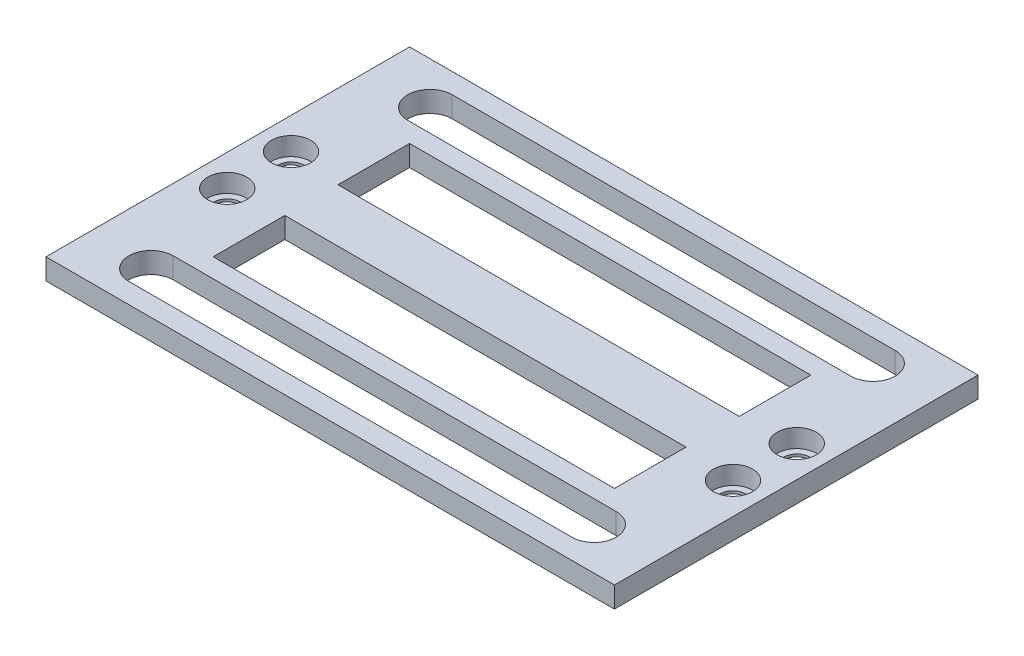
SolidWorks part; units mm, degrees
material "PLA"
ref_plane "Front Plane" through (0, 0, 0) normal (0, 0, 1) x (1, 0, 0)
ref_plane "Top Plane" through (0, 0, 0) normal (0, 1, 0) x (1, 0, 0)
ref_plane "Right Plane" through (0, 0, 0) normal (1, 0, 0) x (0, 0, -1)
sketch "Sketch1" plane through (0, 0, 0) normal (0, 1, 0) x (1, 0, 0)
  line L0 (-27.2, -17.399) -> (-21.2, -17.399) construction
  line L1 (-27.2, -17.399) -> (27.2, -17.399)
  line L2 (-27.2, -17.399) -> (-27.2, 17.399)
  line L3 (-27.2, 17.399) -> (27.2, 17.399)
  line L4 (27.2, -17.399) -> (27.2, 17.399)
  line L5 (-27.2, -17.399) -> (-21.2, -13.561) construction
  line L6 (-27.2, 17.399) -> (17.5466, -11.224) construction
  line L7 (-21.2, -17.399) -> (-21.2, -15.474) construction
  line L8 (-21.2, -15.474) -> (-21.2, -11.224) construction
  line L9 (0, -55) -> (0, 55) construction
  line L10 (-21.2, -11.224) -> (21.2, -11.224)
  line L11 (21.2, -15.474) -> (-21.2, -15.474)
  line L12 (-17.5466, -11.224) -> (27.2, 17.399) construction
  line L13 (22.8875, -14.6405) -> (27.2, -17.399) construction
  line L14 (-55, 0) -> (55, 0) construction
  line L15 (-21.2, 11.224) -> (21.2, 11.224)
  line L16 (21.2, 15.474) -> (-21.2, 15.474)
  line L17 (-21.2, -11.224) -> (-21.2, -9.3952) construction
  line L18 (-21.2, -9.3952) -> (-19.2, -9.3952) construction
  line L19 (19.2, 9.3952) -> (19.2, 2.5452)
  line L20 (-19.2, -9.3952) -> (19.2, -9.3952)
  line L21 (-19.2, -9.3952) -> (-19.2, -2.5452)
  line L22 (-19.2, -2.5452) -> (19.2, -2.5452)
  line L23 (19.2, -9.3952) -> (19.2, -2.5452)
  line L24 (-19.2, 9.3952) -> (19.2, 9.3952)
  line L25 (-19.2, 2.5452) -> (19.2, 2.5452)
  line L26 (-19.2, 9.3952) -> (-19.2, 2.5452)
  arc A0 (-21.2, -11.224) -> (-21.2, -15.474) centre (-21.2, -13.349) ccw
  arc A1 (21.2, -11.224) -> (21.2, -15.474) centre (21.2, -13.349) cw
  arc A2 (-21.2, 11.224) -> (-21.2, 15.474) centre (-21.2, 13.349) cw
  arc A3 (21.2, 11.224) -> (21.2, 15.474) centre (21.2, 13.349) ccw
  point P0 (0, 0)
  dimension "D1" = 54.4
  dimension "D2" = 34.798
  dimension "D3" = 1.925
  dimension "D4" = 6
  dimension "D5" = 4.25
  dimension "D6" = 1.8288
extrude "Boss-Extrude1" add sketch "Sketch1" along normal blind 2
sketch "Sketch2" plane through (0, 2, 0) normal (0, 1, 0) x (1, 0, 0)
  line L0 (-55, 0) -> (55, 0) construction
  line L1 (0, -55) -> (0, 55) construction
  line L9 (-22.325, 2.4962) -> (-22.325, -3.0538) construction
  line L10 (-22.325, -3.0538) -> (-26.075, -3.0538) construction
  line L11 (22.325, -3.0538) -> (26.075, -3.0538) construction
  line L12 (22.325, 2.4962) -> (22.325, -3.0538) construction
  circle A0 centre (-24.2, -3.0538) radius 1.875
  circle A4 centre (-24.2, 3.0538) radius 1.875
  circle A5 centre (24.2, 3.0538) radius 1.875
  circle A6 centre (24.2, -3.0538) radius 1.875
  dimension "D4" = 5.55
  dimension "D5" = 3.75
extrude "Cut-Extrude1" cut sketch "Sketch2" against normal blind 5.55 and the other way through all
sketch "Sketch3" plane through (0, 0, 0) normal (0, -1, 0) x (1, 0, 0)
  line L0 (55, 0) -> (-55, 0) construction
  line L1 (0, -55) -> (0, 55) construction
  circle A0 centre (-24.2, 3.0538) radius 1.875 construction
  circle A1 centre (-24.2, -3.0538) radius 1.875 construction
  circle A2 centre (-24.2, 3.0538) radius 1.875
  circle A3 centre (-24.2, -3.0538) radius 1.875
  circle A4 centre (-24.2, -3.0538) radius 1.25
  circle A5 centre (-24.2, 3.0538) radius 1.25
  circle A6 centre (24.2, 3.0538) radius 1.25
  circle A7 centre (24.2, -3.0538) radius 1.25
  circle A8 centre (24.2, -3.0538) radius 1.875
  circle A9 centre (24.2, 3.0538) radius 1.875
extrude "Boss-Extrude2" add sketch "Sketch3" against normal blind 0.25
